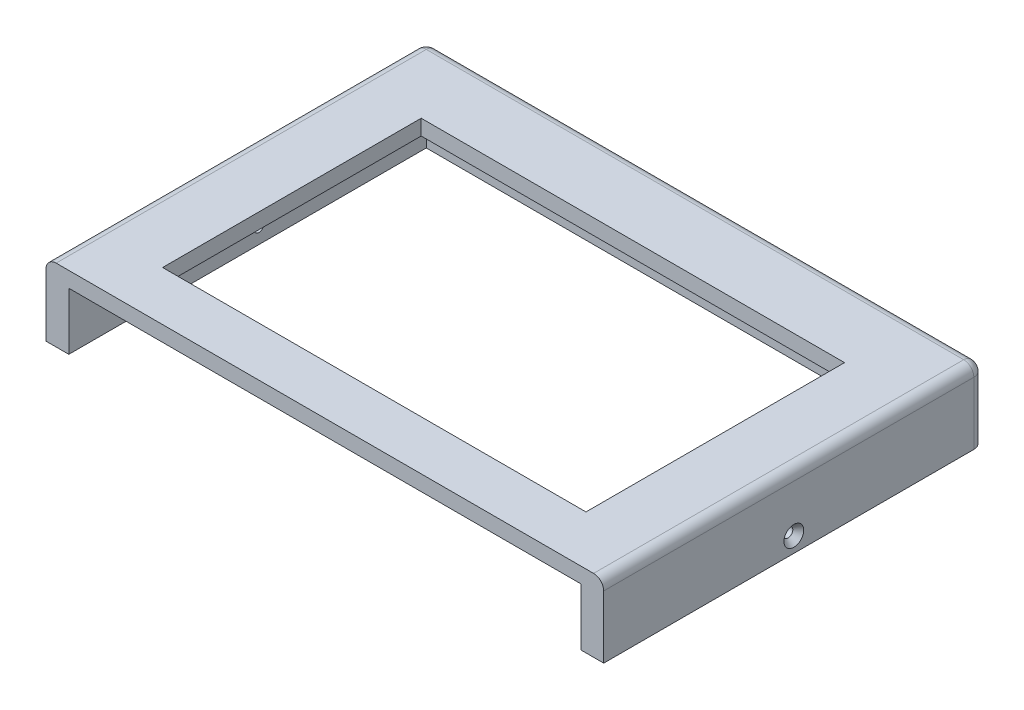
SolidWorks part; units mm, degrees
ref_plane "Front Plane" through (0, 0, 0) normal (0, 0, 1) x (1, 0, 0)
ref_plane "Top Plane" through (0, 0, 0) normal (0, 1, 0) x (1, 0, 0)
ref_plane "Right Plane" through (0, 0, 0) normal (1, 0, 0) x (0, 0, -1)
sketch "Sketch1" plane through (0, 0, 0) normal (0, 1, 0) x (1, 0, 0)
  line L0 (211, 0) -> (220, 0)
  line L2 (9, 0) -> (9, 141)
  line L3 (9, 141) -> (211, 141)
  line L4 (211, 0) -> (211, 141)
  line L5 (220, 0) -> (220, 150)
  line L6 (220, 150) -> (0, 150)
  line L7 (0, 150) -> (0, 0)
  line L8 (0, 0) -> (9, 0)
  point P8 (0, 0)
  point P10 (0, 0)
  dimension "D1" = 220
  dimension "D2" = 141
  dimension "D3" = 202
  dimension "D4" = 150
extrude "Boss-Extrude1" add sketch "Sketch1" along normal blind 22.59
sketch "Sketch2" plane through (0, 22.59, 0) normal (0, 1, 0) x (1, 0, 0)
  line L0 (220, 0) -> (220, 150) construction
  line L1 (0, 150) -> (220, 150)
  line L2 (0, 150) -> (0, 0)
  line L3 (0, 0) -> (220, 0)
  line L4 (220, 150) -> (220, 0)
  line L5 (211, 0) -> (220, 0) construction
  line L6 (9, 141) -> (211, 141) construction
  line L7 (26.5, 121.5) -> (193.5, 121.5)
  line L8 (26.5, 121.5) -> (26.5, 19.5)
  line L9 (26.5, 19.5) -> (193.5, 19.5)
  line L10 (193.5, 121.5) -> (193.5, 19.5)
  line L11 (211, 141) -> (211, 0) construction
  point P15 (110, 141)
  point P16 (110, 121.5)
  point P19 (211, 70.5)
  point P20 (193.5, 70.5)
  dimension "D1" = 167
  dimension "D2" = 102
extrude "Boss-Extrude2" add sketch "Sketch2" along normal blind 6.08
hole_wizard "CSK for #6 Flat Head Socket Cap Screw2" positions "Sketch7" profile "Sketch8" countersink size "#6" standard "ANSI Inch"
sketch "Sketch7" plane through (220, 0, 0) normal (1, 0, 0) x (0, 0, -1)
  line L0 (0, 0) -> (150, 0) construction
  point P0 (75, 6)
  point P3 (75, 0)
  dimension "D1" = 6
sketch "Sketch8" plane through (220, 6, -75) normal (0, 1, 0) x (0, 0, -1)
  line L0 (0, 0) -> (0, 9)
  line L1 (0, 9) -> (1.8986, 9)
  line L2 (1.8986, 9) -> (1.8986, 2.301)
  line L3 (1.8986, 2.301) -> (3.8989, 0)
  line L5 (3.8989, 0) -> (0, 0)
  line L6 (-1.8987, 2.301) -> (-3.8989, 0) construction
  line L11 (0, -6.35) -> (0, 107.95) construction
  dimension "Thru Hole Dia." = 3.7973
  dimension "Thru Hole Depth" = 9
  dimension "Near C'Sink Dia." = 7.7978
  dimension "Near C'Sink Angle" = 82
hole_wizard "CSK for #6 Flat Head Socket Cap Screw3" positions "Sketch9" profile "Sketch10" countersink size "#6" standard "ANSI Inch" end condition up to next
sketch "Sketch9" plane through (0, 0, -150) normal (0, 0, -1) x (-1, 0, 0)
  line L0 (-220, 0) -> (0, 0) construction
  point P0 (-110, 6)
  point P5 (0, 0)
  point P6 (-110, 0)
  dimension "D1" = 6
sketch "Sketch10" plane through (110, 6, -150) normal (1, 0, 0) x (0, 1, 0)
  line L0 (0, 0) -> (0, 9)
  line L1 (0, 9) -> (1.8986, 9)
  line L2 (1.8986, 9) -> (1.8986, 2.301)
  line L3 (1.8986, 2.301) -> (3.8989, 0)
  line L5 (3.8989, 0) -> (0, 0)
  line L6 (-1.8986, 2.301) -> (-3.8989, 0) construction
  line L11 (0, -6.35) -> (0, 107.95) construction
  dimension "Thru Hole Dia." = 3.7973
  dimension "Thru Hole Depth" = 9
  dimension "Near C'Sink Dia." = 7.7978
  dimension "Near C'Sink Angle" = 82
hole_wizard "CSK for #6 Flat Head Socket Cap Screw4" positions "Sketch11" profile "Sketch12" countersink size "#6" standard "ANSI Inch" end condition up to next
sketch "Sketch11" plane through (0, 0, 0) normal (-1, 0, 0) x (0, 0, 1)
  line L0 (-150, 0) -> (0, 0) construction
  point P0 (-75, 6)
  point P9 (-77.3855, 5.9227)
  point P10 (0, 0)
  point P11 (-75, 0)
  dimension "D1" = 6
sketch "Sketch12" plane through (0, 6, -75) normal (0, 1, 0) x (0, 0, 1)
  line L0 (0, 0) -> (0, 9)
  line L1 (0, 9) -> (1.8986, 9)
  line L2 (1.8986, 9) -> (1.8986, 2.301)
  line L3 (1.8986, 2.301) -> (3.8989, 0)
  line L5 (3.8989, 0) -> (0, 0)
  line L6 (-1.8986, 2.301) -> (-3.8989, 0) construction
  line L11 (0, -6.35) -> (0, 107.95) construction
  dimension "Thru Hole Dia." = 3.7973
  dimension "Thru Hole Depth" = 9
  dimension "Near C'Sink Dia." = 7.7978
  dimension "Near C'Sink Angle" = 82
fillet "Fillet1" radius 4 5 edges at (0, 14.335, -150) (0, 28.67, -75) (220, 14.335, -150) (110, 28.67, -150) (220, 28.67, -75)
